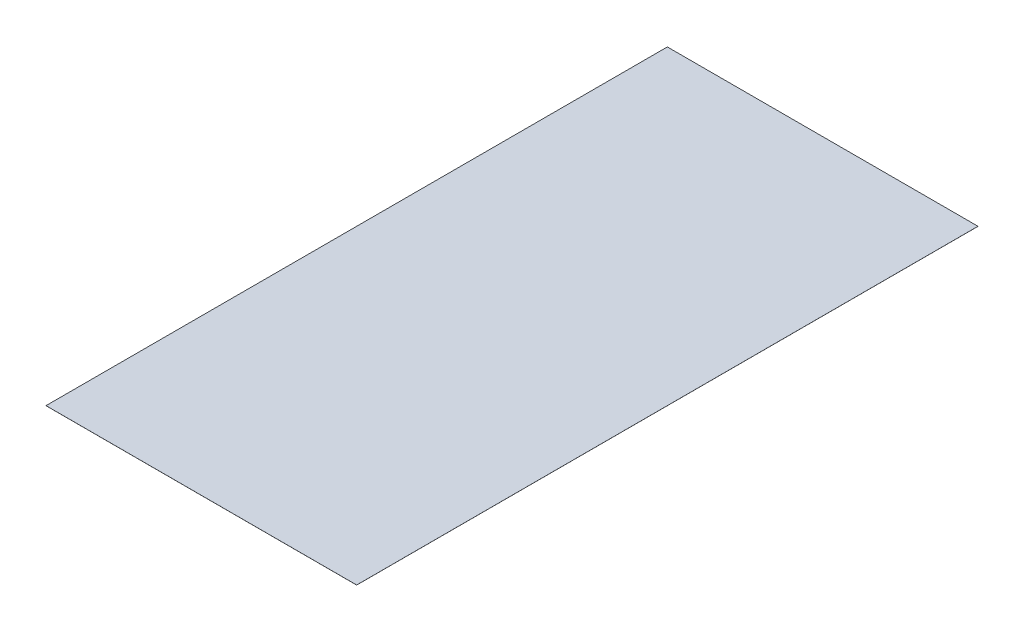
SolidWorks part; units mm, degrees
ref_plane "Front Plane" through (0, 0, 0) normal (0, 0, 1) x (1, 0, 0)
ref_plane "Top Plane" through (0, 0, 0) normal (0, 1, 0) x (1, 0, 0)
ref_plane "Right Plane" through (0, 0, 0) normal (1, 0, 0) x (0, 0, -1)
sketch "Sketch1" plane through (0, 0, 0) normal (0, 1, 0) x (1, 0, 0)
  line L1 (-2500, -5000) -> (2500, -5000)
  line L2 (-2500, -5000) -> (-2500, 5000)
  line L3 (-2500, 5000) -> (2500, 5000)
  line L4 (2500, -5000) -> (2500, 5000)
  line L5 (-2500, -5000) -> (2500, 5000) construction
  line L6 (-2500, 5000) -> (2500, -5000) construction
  point P0 (0, 0)
  dimension "D1" = 10000
  dimension "D2" = 5000
extrude "Boss-Extrude1" add sketch "Sketch1" along normal blind 1
